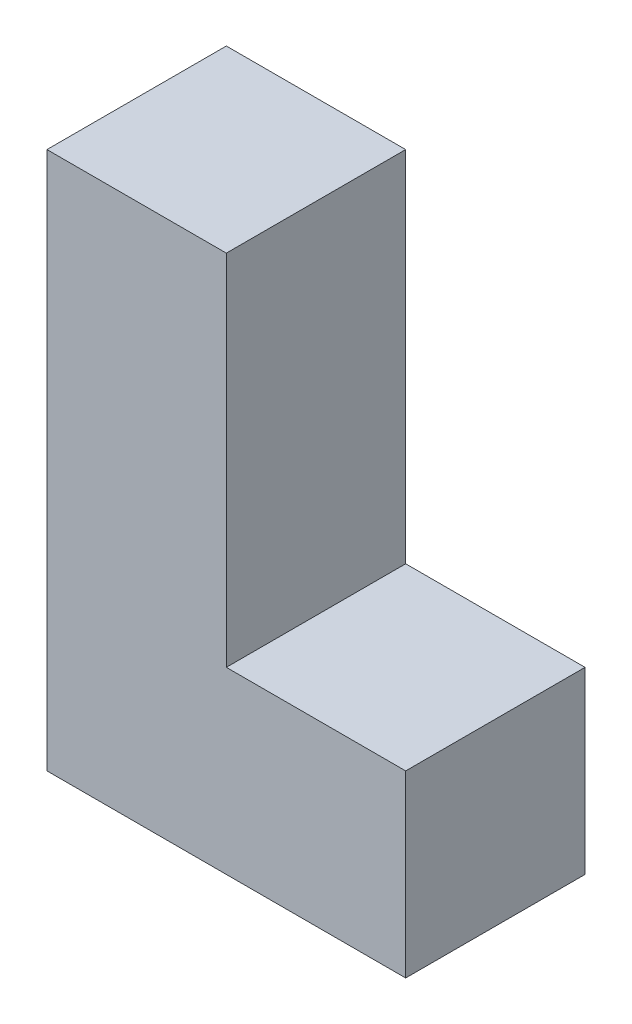
SolidWorks part; units mm, degrees
ref_plane "Plan de face" through (0, 0, 0) normal (0, 0, 1) x (1, 0, 0)
ref_plane "Plan de dessus" through (0, 0, 0) normal (0, 1, 0) x (1, 0, 0)
ref_plane "Plan de droite" through (0, 0, 0) normal (1, 0, 0) x (0, 0, -1)
sketch "Esquisse1" plane through (0, 0, 0) normal (0, 0, 1) x (1, 0, 0)
  line L0 (0, 0) -> (0, 30)
  line L1 (10, 30) -> (10, 10)
  line L2 (10, 10) -> (20, 10)
  line L3 (20, 10) -> (20, 0)
  line L4 (0, 0) -> (20, 0)
  line L5 (10, 30) -> (0, 30)
  dimension "D1" = 10
  dimension "D2" = 20
  dimension "D3" = 30
  dimension "D4" = 10
extrude "Boss.-Extru.1" add sketch "Esquisse1" against normal blind 10
